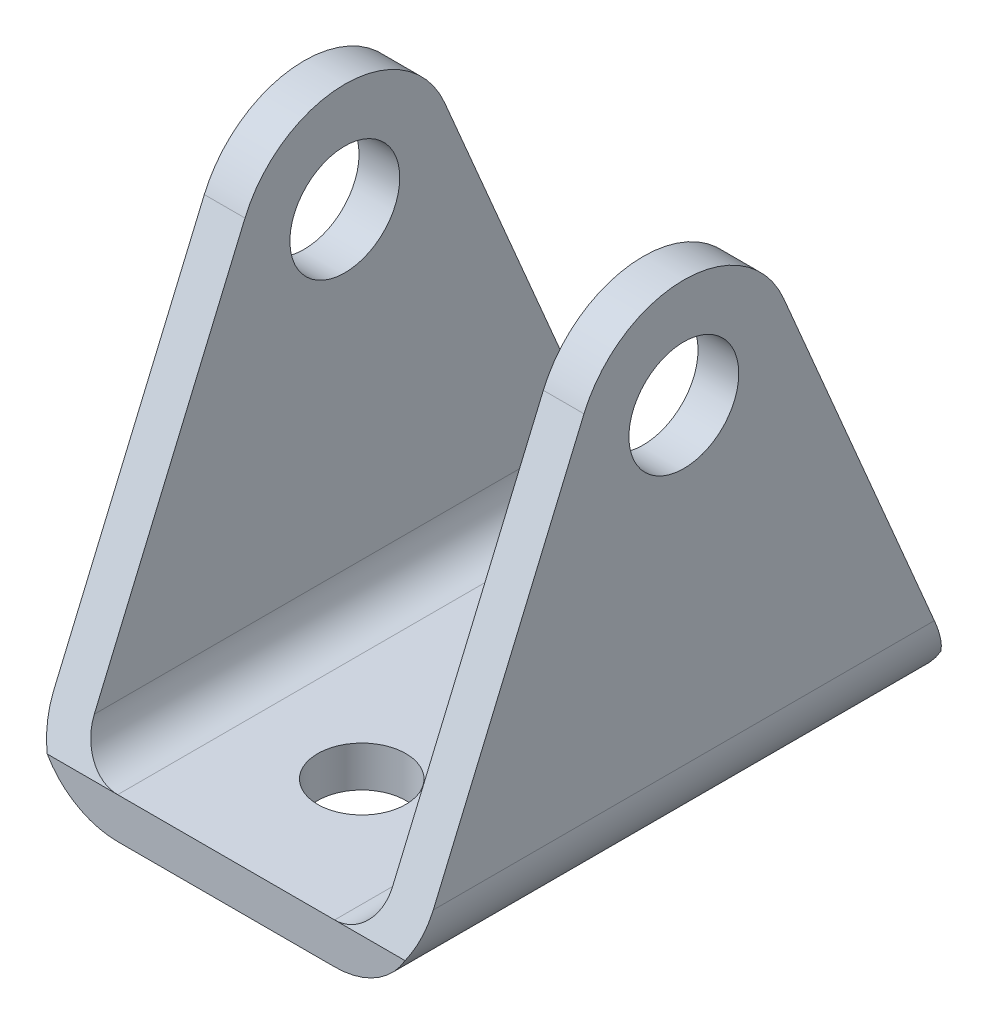
SolidWorks part; units mm, degrees
material "3003 Alloy"
ref_plane "Front Plane" through (0, 0, 0) normal (0, 0, 1) x (1, 0, 0)
ref_plane "Top Plane" through (0, 0, 0) normal (0, 1, 0) x (1, 0, 0)
ref_plane "Right Plane" through (0, 0, 0) normal (1, 0, 0) x (0, 0, -1)
sketch "Sketch1" plane through (0, 0, 0) normal (0, 1, 0) x (1, 0, 0)
  line L0 (0, 26.0471) -> (0, -33.7754) construction
  line L1 (-11, -19.75) -> (11, -19.75)
  line L2 (-11, -19.75) -> (-11, 19.75)
  line L3 (-11, 19.75) -> (-4.25, 19.75)
  line L4 (11, -19.75) -> (11, 19.75)
  line L5 (-11, -19.75) -> (11, 19.75) construction
  line L6 (-11, 19.75) -> (11, -19.75) construction
  line L7 (3.25, 12.25) -> (3.25, 18.75)
  line L8 (-3.25, 12.25) -> (-3.25, 18.75)
  line L9 (4.25, 19.75) -> (11, 19.75)
  arc A0 (-3.25, 12.25) -> (3.25, 12.25) centre (0, 12.25) ccw
  circle A1 centre (0, -9.75) radius 3.25
  arc A2 (3.25, 18.75) -> (4.25, 19.75) centre (4.25, 18.75) cw
  arc A3 (-3.25, 18.75) -> (-4.25, 19.75) centre (-4.25, 18.75) ccw
  point P0 (0, 0)
  point P17 (3.25, 19.75)
  dimension "D5" = 6.5
  dimension "D6" = 1
  dimension "D1" = 39.5
  dimension "D2" = 22
  dimension "D3" = 7.5
  dimension "D4" = 22
extrude "Boss-Extrude1" add sketch "Sketch1" along normal blind 3
sketch "Sketch2" plane through (11, 0, 0) normal (1, 0, 0) x (0, 0, -1)
  line L0 (0, -14.914) -> (0, 89.079) construction
  line L1 (-19.75, 3) -> (-7.362, 32.1307)
  line L2 (19.75, 3) -> (7.362, 32.1307)
  line L3 (-30.5523, 37) -> (28.8026, 37) construction
  line L4 (-19.75, 0) -> (19.75, 0)
  line L5 (19.75, 0) -> (19.75, 3)
  line L6 (19.75, 3) -> (-19.75, 3)
  line L7 (-19.75, 3) -> (-19.75, 0)
  line L8 (-19.75, 0) -> (19.75, 0)
  line L9 (19.75, 0) -> (19.75, 3)
  line L10 (19.75, 3) -> (0, 3) construction
  line L11 (-19.75, 3) -> (-19.75, 0)
  line L12 (0, 3) -> (-19.75, 3) construction
  circle A0 centre (0, 29) radius 4.05
  arc A1 (7.362, 32.1307) -> (-7.362, 32.1307) centre (0, 29) ccw
  arc A2 (0, 21) -> (7.362, 32.1307) centre (0, 29) ccw construction
  arc A3 (-7.362, 32.1307) -> (0, 21) centre (0, 29) ccw construction
  dimension "D2" = 8.1
  dimension "D3" = 29
  dimension "D4" = 37
  dimension "D1" = 0
extrude "Boss-Extrude2" add sketch "Sketch2" along normal blind 3
mirror "Mirror1" about plane through (0, 0, 0) normal (1, 0, 0) of "Boss-Extrude2"
fillet "Fillet1" radius 6 2 edges at (-14, 0, 0) (14, 0, 0)
fillet "Fillet2" radius 3 2 edges at (11, 3, 0) (-11, 3, 0)
